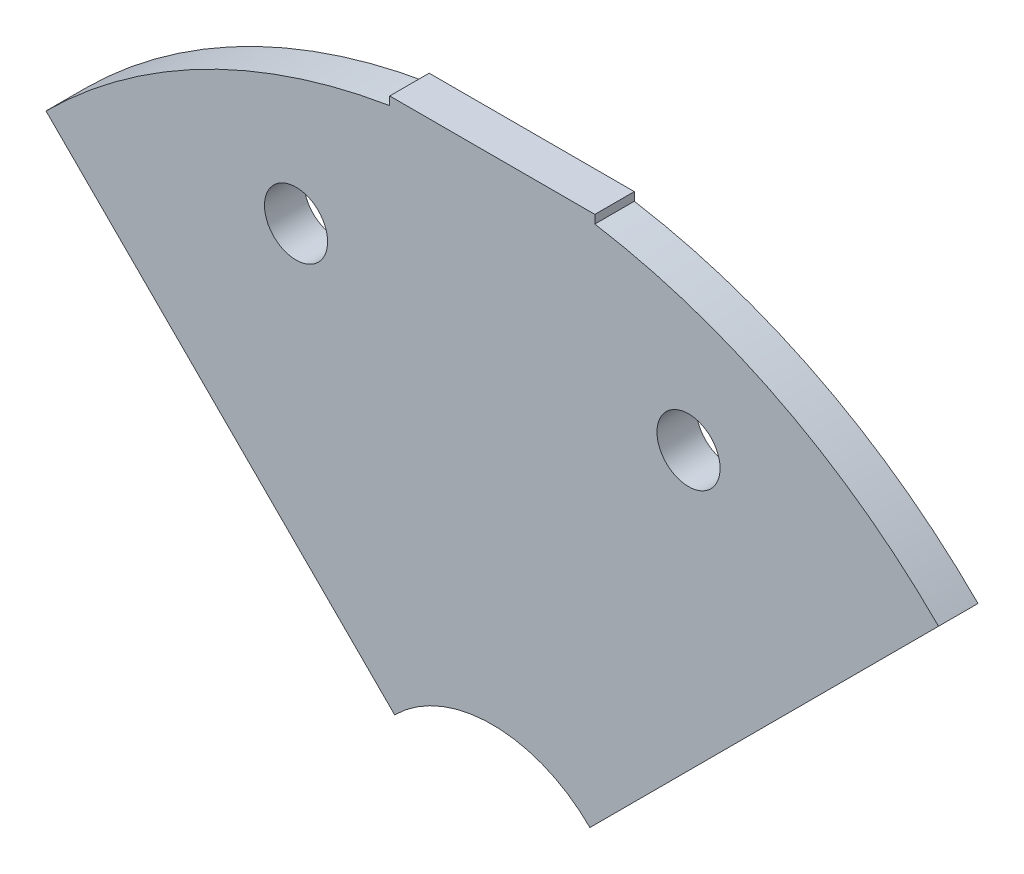
SolidWorks part; units mm, degrees
material "Plain Carbon Steel"
ref_plane "Front Plane" through (0, 0, 0) normal (0, 0, 1) x (1, 0, 0)
ref_plane "Top Plane" through (0, 0, 0) normal (0, 1, 0) x (1, 0, 0)
ref_plane "Right Plane" through (0, 0, 0) normal (1, 0, 0) x (0, 0, -1)
sketch "Sketch1" plane through (0, 0, 0) normal (0, 0, 1) x (1, 0, 0)
  line L0 (0, -55) -> (0, 55) construction
  line L3 (-80, 0) -> (-17.5, 0)
  line L5 (-60.0522, 24.8744) -> (0, 0) construction
  line L6 (0, 0) -> (60.0522, 24.8744) construction
  line L7 (55, 0) -> (-55, 0) construction
  line L8 (17.5, 0) -> (80, 0)
  line L9 (24.8744, 60.0522) -> (0, 0) construction
  arc A0 (17.5, 0) -> (-17.5, 0) centre (0, 0) ccw
  circle A1 centre (24.8744, 60.0522) radius 4
  circle A12 centre (60.0522, 24.8744) radius 4
  arc A15 (80, 0) -> (-80, 0) centre (0, 0) ccw
  circle A17 centre (-60.0522, 24.8744) radius 4
  circle A18 centre (-24.8744, 60.0522) radius 4
  point P0 (0, 0)
  point P26 (0, -19.4444)
  point P27 (0, 0)
  point P29 (0, 0)
  dimension "D1" = 22.5
  dimension "D4" = 8
  dimension "D7" = 80
  dimension "D8" = 35
  dimension "D2" = 22.5
  dimension "D3" = 65
  dimension "D5" = 65
  dimension "D6" = 65
  dimension "D9" = 22.5
extrude "Boss-Extrude1" add sketch "Sketch1" along normal blind 5
sketch "Sketch2" plane through (0, 0, 0) normal (0, 0, 1) x (1, 0, 0)
  line L0 (-12.3744, 12.3744) -> (-56.5685, 56.5685)
  line L1 (-56.5685, 56.5685) -> (-80, 56.5685)
  line L2 (-80, 56.5685) -> (-80, 0)
  line L3 (-80, 0) -> (-17.5, 0)
  line L4 (80, 0) -> (80, 56.5685)
  line L5 (80, 56.5685) -> (56.5685, 56.5685)
  line L6 (56.5685, 56.5685) -> (12.3744, 12.3744)
  line L7 (55, 0) -> (-55, 0) construction
  line L8 (17.5, 0) -> (80, 0)
  arc A0 (80, 0) -> (-80, 0) centre (0, 0) ccw construction
  arc A1 (17.5, 0) -> (12.3744, 12.3744) centre (0, 0) ccw
  arc A2 (-12.3744, 12.3744) -> (-17.5, 0) centre (0, 0) ccw
  dimension "D1" = 17.5
extrude "Cut-Extrude1" cut sketch "Sketch2" along normal through all
sketch "Sketch3" plane through (0, 0, 0) normal (0, 0, 1) x (1, 0, 0)
  line L0 (0, -2.75) -> (0, 2.75) construction
  line L1 (-13, 78.9367) -> (13, 78.9367)
  line L2 (-13, 78.9367) -> (-13, 80)
  line L3 (-13, 80) -> (13, 80)
  line L4 (13, 78.9367) -> (13, 80)
  line L5 (-13, 78.9367) -> (13, 80) construction
  line L6 (-13, 80) -> (13, 78.9367) construction
  arc A0 (56.5685, 56.5685) -> (-56.5685, 56.5685) centre (0, 0) ccw construction
  point P0 (0, 79.4683)
  point P5 (0, 80)
  dimension "D1" = 26
extrude "Boss-Extrude2" add sketch "Sketch3" along normal blind 5
